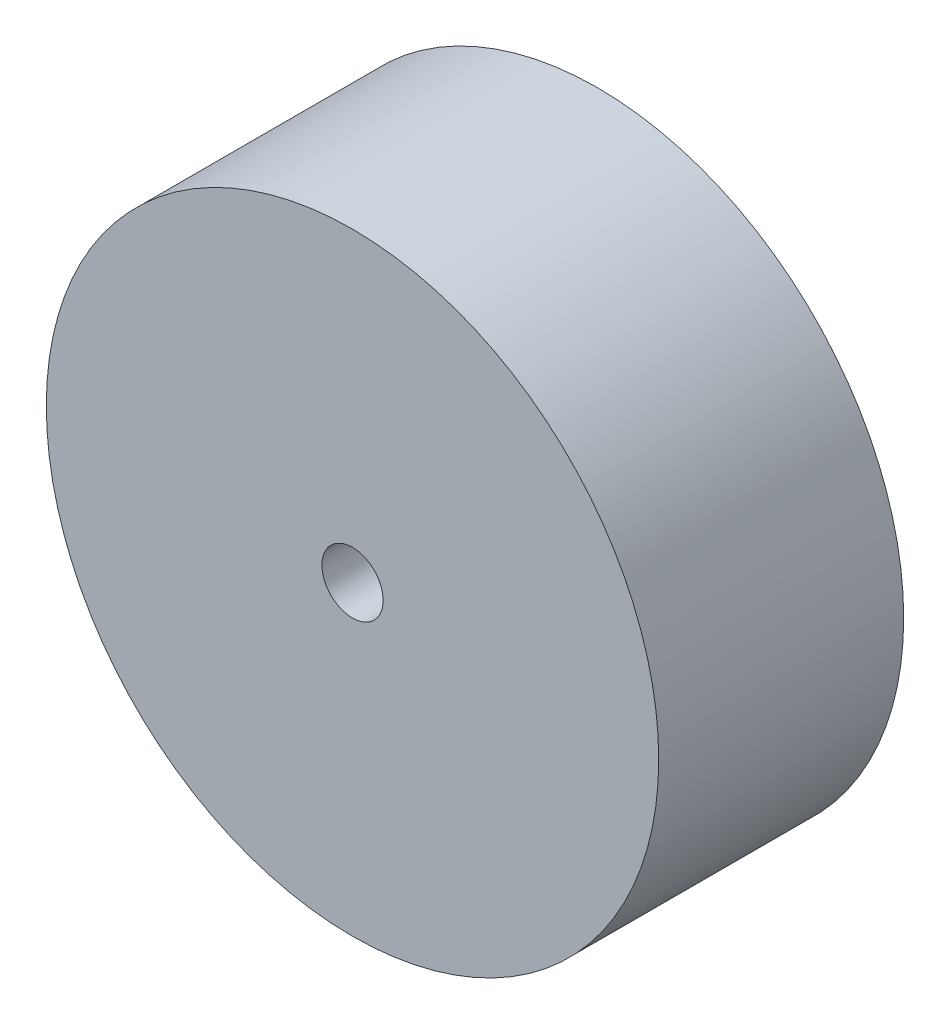
SolidWorks part; units mm, degrees
ref_plane "Plan de face" through (0, 0, 0) normal (0, 0, 1) x (1, 0, 0)
ref_plane "Plan de dessus" through (0, 0, 0) normal (0, 1, 0) x (1, 0, 0)
ref_plane "Plan de droite" through (0, 0, 0) normal (1, 0, 0) x (0, 0, -1)
sketch "Esquisse1" plane through (0, 0, 0) normal (0, 0, 1) x (1, 0, 0)
  circle A0 centre (0, 0) radius 25
  circle A1 centre (0, 0) radius 2.5
  dimension "D1" = 5
  dimension "D2" = 50
extrude "Extrusion1" add sketch "Esquisse1" along normal blind 20
